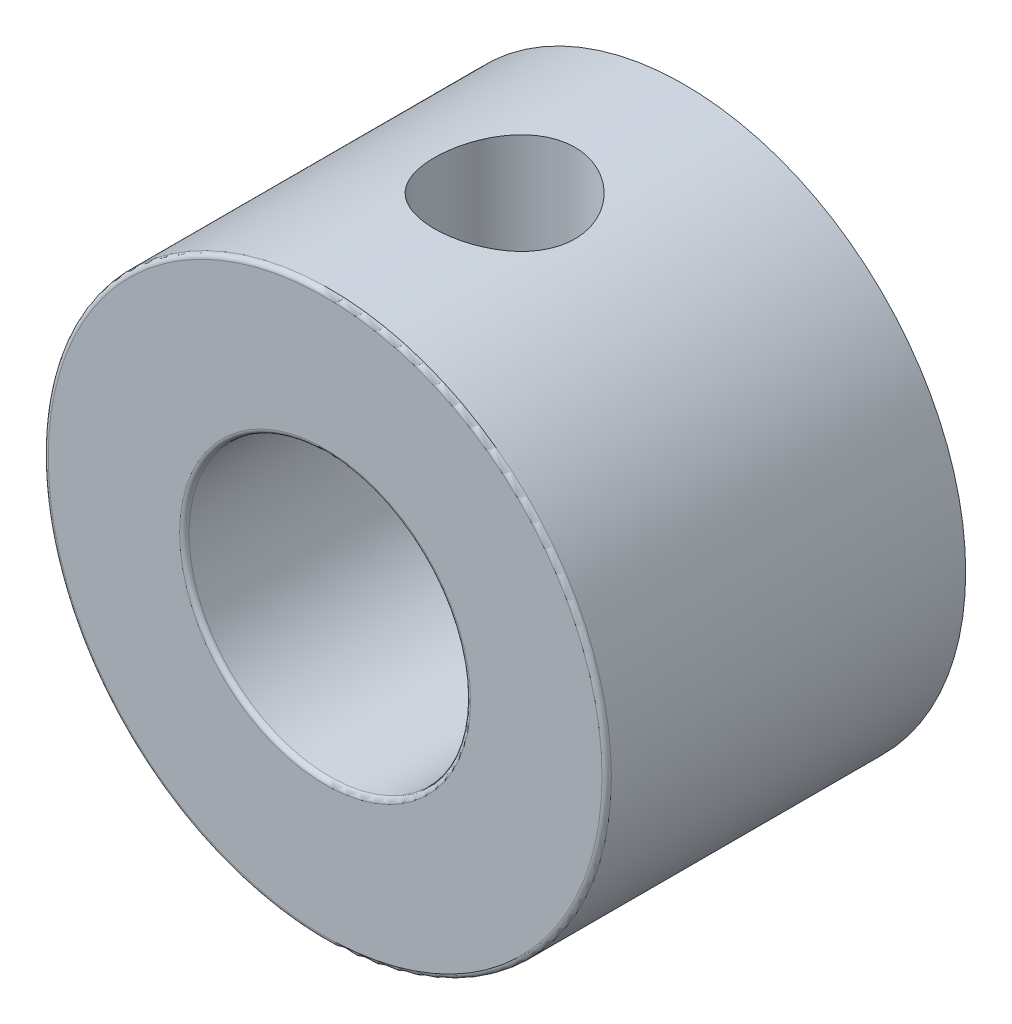
SolidWorks part; units mm, degrees
ref_plane "前基準面" through (0, 0, 0) normal (0, 0, 1) x (1, 0, 0)
ref_plane "上基準面" through (0, 0, 0) normal (0, 1, 0) x (1, 0, 0)
ref_plane "右基準面" through (0, 0, 0) normal (1, 0, 0) x (0, 0, -1)
sketch "草圖1" plane through (0, 0, 0) normal (0, 0, 1) x (1, 0, 0)
  circle A0 centre (0, 0) radius 6
  circle A1 centre (0, 0) radius 3
  dimension "D1" = 6
  dimension "D2" = 12
extrude "填料-伸長1" add sketch "草圖1" along normal mid plane 7.65
fillet "圓角1" radius 0.1 3 edges at (3, 0, -3.825) (3, 0, 3.825) (6, 0, 3.825)
sketch "草圖2" plane through (0, 0, 0) normal (0, 1, 0) x (1, 0, 0)
  circle A0 centre (0, 0) radius 1.5
  dimension "D1" = 3
extrude "除料-伸長1" cut sketch "草圖2" along normal blind 7.65
